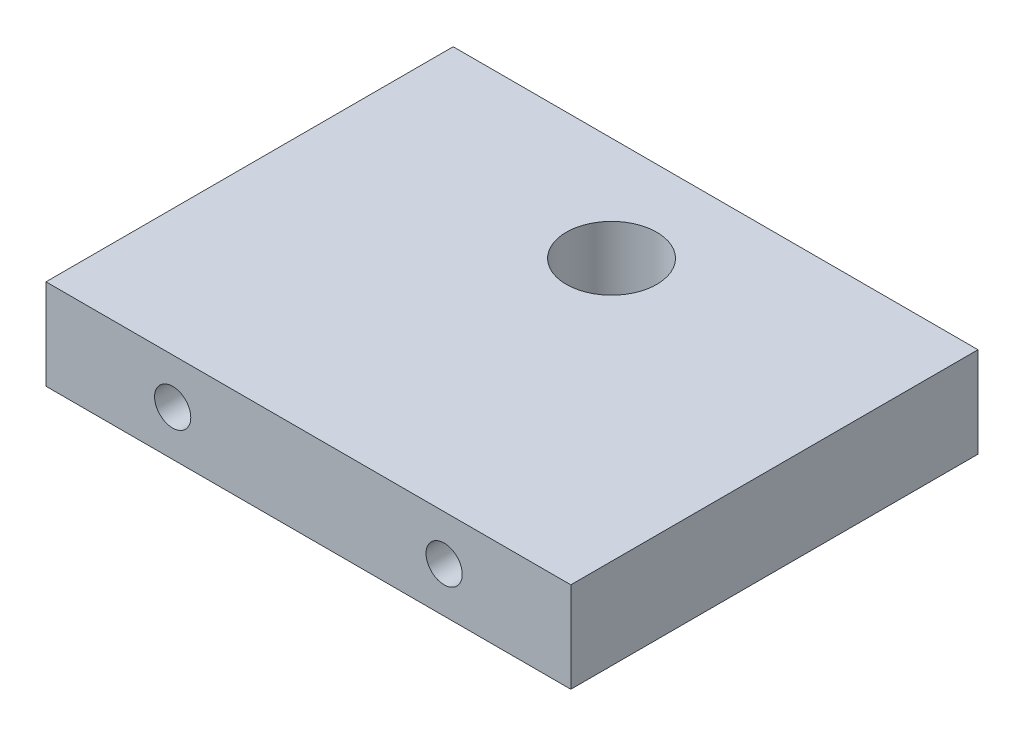
SolidWorks part; units mm, degrees
ref_plane "Front Plane" through (0, 0, 0) normal (0, 0, 1) x (1, 0, 0)
ref_plane "Top Plane" through (0, 0, 0) normal (0, 1, 0) x (1, 0, 0)
ref_plane "Right Plane" through (0, 0, 0) normal (1, 0, 0) x (0, 0, -1)
sketch "Sketch1" plane through (0, 0, 0) normal (0, 0, 1) x (1, 0, 0)
  line L1 (0, 0) -> (58, 0)
  line L2 (0, 0) -> (0, -10)
  line L3 (0, -10) -> (58, -10)
  line L4 (58, 0) -> (58, -10)
  circle A0 centre (14, -5) radius 2
  circle A1 centre (44, -5) radius 2
  dimension "D4" = 14
  dimension "D5" = 5
  dimension "D6" = 14
  dimension "D7" = 4
  dimension "D8" = 4
  dimension "D1" = 58
  dimension "D2" = 10
  dimension "D3" = 5
extrude "Boss-Extrude1" add sketch "Sketch1" along normal blind 55
sketch "Sketch3" plane through (0, 0, 0) normal (0, 0, -1) x (-1, 0, 0)
  line L4 (0, -10) -> (0, 0)
  line L5 (0, 0) -> (-58, 0)
  line L6 (-58, 0) -> (-58, -10)
  line L7 (-58, -10) -> (0, -10)
  line L8 (0, -10) -> (0, 0)
  line L9 (0, 0) -> (-58, 0)
  line L10 (-58, 0) -> (-58, -10)
  line L11 (-58, -10) -> (0, -10)
  dimension "D1" = 0
extrude "Cut-Extrude3" cut sketch "Sketch3" against normal blind 10
sketch "Sketch4" plane through (0, 0, 0) normal (0, 1, 0) x (1, 0, 0)
  line L0 (0, -10) -> (58, -10) construction
  circle A0 centre (29, -21.5) radius 5
  point P5 (29, -10)
  dimension "D1" = 10
  dimension "D2" = 11.5
extrude "Cut-Extrude4" cut sketch "Sketch4" against normal blind 10
